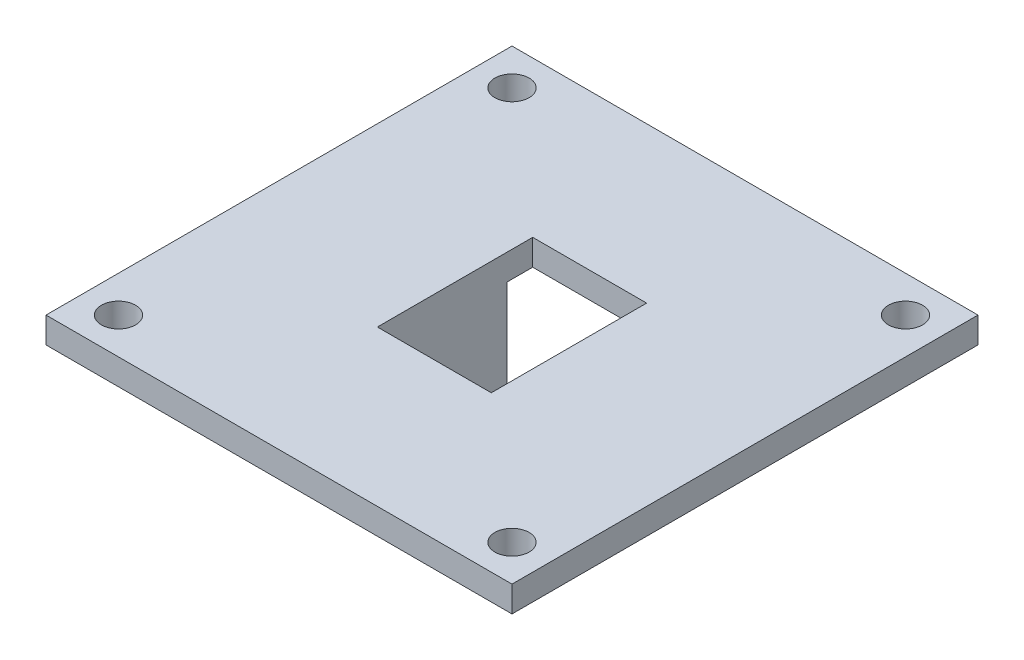
SolidWorks part; units mm, degrees
ref_plane "前视基准面" through (0, 0, 0) normal (0, 0, 1) x (1, 0, 0)
ref_plane "上视基准面" through (0, 0, 0) normal (0, 1, 0) x (1, 0, 0)
ref_plane "右视基准面" through (0, 0, 0) normal (1, 0, 0) x (0, 0, -1)
other "Configuration Table"
sketch "草图1" plane through (0, 0, 0) normal (0, 1, 0) x (1, 0, 0)
  circle A0 centre (0, 0) radius 19
extrude "凸台-拉伸1" add sketch "草图1" along normal blind 3
sketch "草图2" plane through (0, 3, 0) normal (0, 1, 0) x (1, 0, 0)
  circle A0 centre (-5, 0) radius 1.6
  circle A1 centre (0, 0) radius 1.6
  circle A2 centre (5, 0) radius 1.6
  circle A3 centre (0, -5) radius 1.6
  point P0 (5, 0)
  point P1 (0, 0)
  point P2 (-5, 0)
  point P4 (0, -5)
  dimension "D1" = 5
  dimension "D2" = 5
  dimension "D3" = 5
extrude "切除-拉伸1" cut sketch "草图2" against normal up to next
sketch "草图3" plane through (0, 3, 0) normal (0, 1, 0) x (1, 0, 0)
  line L1 (-15, 10) -> (-11, 10)
  line L2 (-15, 10) -> (-15, -10)
  line L3 (-15, -10) -> (-11, -10)
  line L4 (-11, 10) -> (-11, -10)
  line L5 (-15, 10) -> (-11, -10) construction
  line L6 (-15, -10) -> (-11, 10) construction
  line L7 (11, 10) -> (15, 10)
  line L8 (11, 10) -> (11, -10)
  line L9 (11, -10) -> (15, -10)
  line L10 (15, 10) -> (15, -10)
  line L11 (11, 10) -> (15, -10) construction
  line L12 (11, -10) -> (15, 10) construction
  point P0 (-13, 0)
  point P1 (13, 0)
  point P2 (-13, 0)
  point P8 (13, 0)
  dimension "D1" = 13
  dimension "D2" = 13
  dimension "D3" = 20
  dimension "5" = 4
  dimension "D5" = 20
  dimension "D6" = 4
extrude "凸台-拉伸2" add sketch "草图3" along normal blind 20
sketch "草图4" plane through (0, 23, 0) normal (0, 1, 0) x (1, 0, 0)
  line L1 (-45, 45) -> (45, 45)
  line L2 (-45, 45) -> (-45, -45)
  line L3 (-45, -45) -> (45, -45)
  line L4 (45, 45) -> (45, -45)
  line L5 (-45, 45) -> (45, -45) construction
  line L6 (-45, -45) -> (45, 45) construction
  point P0 (0, 0)
  point P1 (0, 0)
  dimension "D1" = 90
  dimension "D2" = 90
extrude "凸台-拉伸3" add sketch "草图4" along normal blind 5
sketch "草图5" plane through (0, 28, 0) normal (0, 1, 0) x (1, 0, 0)
  line L1 (-38, 38) -> (38, 38) construction
  line L2 (-38, 38) -> (-38, -38) construction
  line L3 (-38, -38) -> (38, -38) construction
  line L4 (38, 38) -> (38, -38) construction
  line L5 (-38, 38) -> (38, -38) construction
  line L6 (-38, -38) -> (38, 38) construction
  circle A0 centre (-38, 38) radius 3.3
  circle A1 centre (38, 38) radius 3.3
  circle A2 centre (-38, -38) radius 3.3
  circle A3 centre (38, -38) radius 3.3
  point P0 (0, 0)
  dimension "D1" = 76
  dimension "D2" = 76
extrude "切除-拉伸2" cut sketch "草图5" against normal through all both and the other way through all
sketch "草图6" plane through (0, 28, 0) normal (0, 1, 0) x (1, 0, 0)
  line L1 (-11, 15) -> (11, 15)
  line L2 (-11, 15) -> (-11, -15)
  line L3 (-11, -15) -> (11, -15)
  line L4 (11, 15) -> (11, -15)
  line L5 (-11, 15) -> (11, -15) construction
  line L6 (-11, -15) -> (11, 15) construction
  point P0 (0, 0)
extrude "切除-拉伸3" cut sketch "草图6" against normal up to surface (5 mm away) and the other way through all up to face at (38, 23, -34.7)
